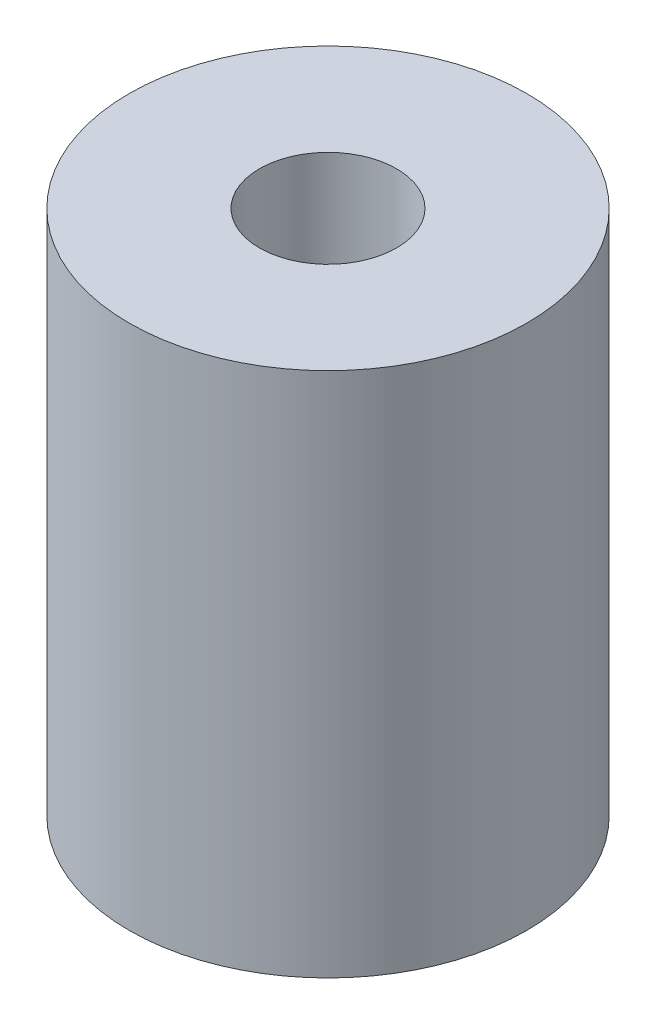
SolidWorks part; units mm, degrees
ref_plane "Front" through (0, 0, 0) normal (0, 0, 1) x (1, 0, 0)
ref_plane "Top" through (0, 0, 0) normal (0, 1, 0) x (1, 0, 0)
ref_plane "Right" through (0, 0, 0) normal (1, 0, 0) x (0, 0, -1)
sketch "Sketch1" plane through (0, 0, 0) normal (0, 1, 0) x (1, 0, 0)
  circle A0 centre (0, 0) radius 3.9751
  dimension "D1" = 7.9502
extrude "Boss-Extrude1" add sketch "Sketch1" along normal blind 10.5156
sketch "Sketch2" plane through (0, 10.5156, 0) normal (0, 1, 0) x (1, 0, 0)
  circle A0 centre (0, 0) radius 1.3716
  dimension "D1" = 2.7432
extrude "Cut-Extrude1" cut sketch "Sketch2" against normal through all
